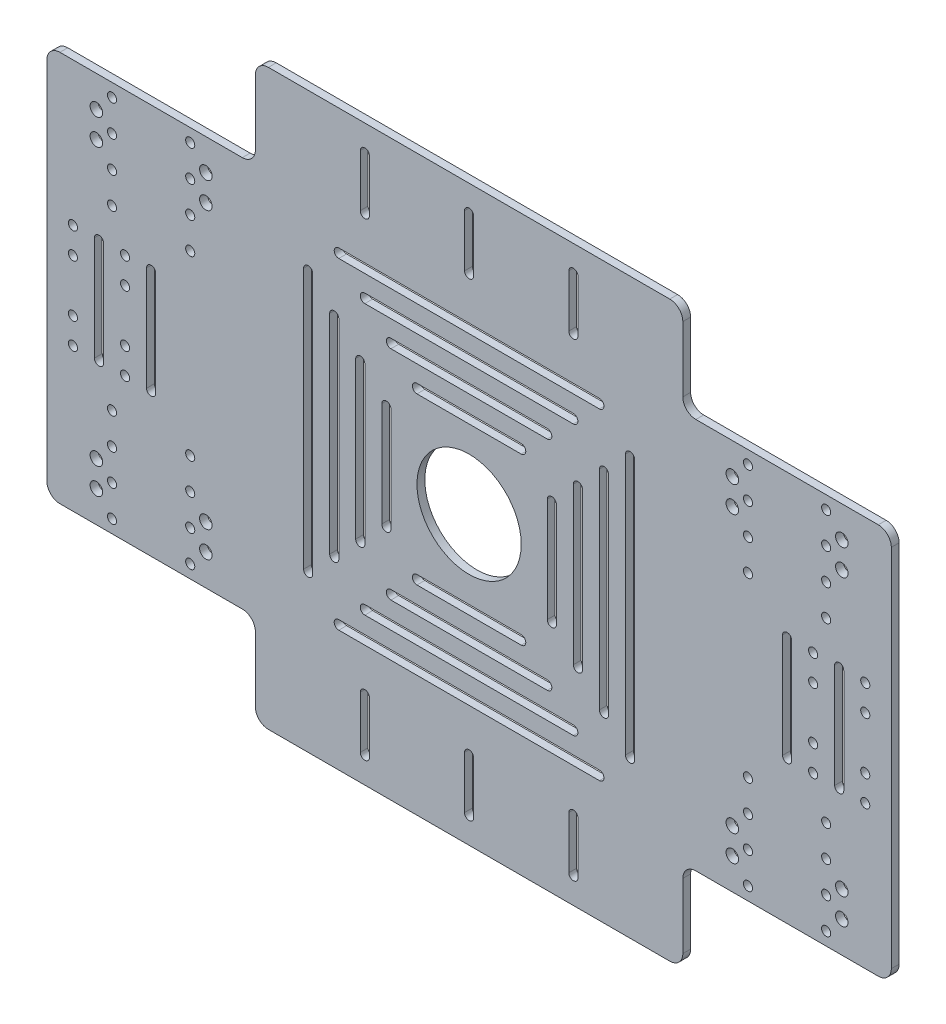
SolidWorks part; units mm, degrees
ref_plane "Front Plane" through (0, 0, 0) normal (0, 0, 1) x (1, 0, 0)
ref_plane "Top Plane" through (0, 0, 0) normal (0, 1, 0) x (1, 0, 0)
ref_plane "Right Plane" through (0, 0, 0) normal (1, 0, 0) x (0, 0, -1)
sketch "Model" plane through (0, 0, 0) normal (0, 0, 1) x (1, 0, 0)
  line L0 (-287, 200) -> (-287, -200)
  line L1 (-287, -200) -> (287, -200)
  line L2 (287, -200) -> (287, 200)
  line L3 (287, 200) -> (-287, 200)
  line L4 (287, -200) -> (287, -144)
  line L5 (287, -144) -> (107, -144)
  line L6 (107, -144) -> (107, -200)
  line L7 (287, -200) -> (107, -200)
  line L8 (187, -144) -> (187, -200)
  line L9 (237, -144) -> (237, -200)
  line L10 (187, -193) -> (107, -193)
  line L11 (187, -186) -> (107, -186)
  line L12 (187, -179) -> (107, -179)
  line L13 (147, -172) -> (147, -200)
  line L14 (213, -172) -> (213, -191)
  line L15 (225, -172) -> (225, -191)
  line L16 (237, -172) -> (107, -172)
  line L17 (287, -179) -> (237, -179)
  line L18 (287, -161) -> (237, -161)
  line L19 (287, -191) -> (187, -191)
  line L20 (-119.2105, 180.4807) -> (-119.2105, 155.4807)
  line L21 (-119.2105, -4.5193) -> (-119.2105, -29.5193)
  line L22 (44.7895, -29.5193) -> (44.7895, -4.5193)
  line L23 (44.7895, 155.4807) -> (44.7895, 180.4807)
  line L24 (39.7895, 185.4807) -> (-99.2105, 185.4807)
  line L25 (-99.2105, 185.4807) -> (-114.2105, 185.4807)
  line L26 (-114.2105, -34.5193) -> (-96.2105, -34.5193)
  line L27 (-96.2105, -34.5193) -> (39.7895, -34.5193)
  line L28 (124.7895, 5.4807) -> (124.7895, 76.9807)
  line L29 (124.7895, 76.9807) -> (124.7895, 145.4807)
  line L30 (-199.2105, 145.4807) -> (-199.2105, 76.9807)
  line L31 (-199.2105, 76.9807) -> (-199.2105, 5.4807)
  line L32 (-124.2105, 150.4807) -> (-194.2105, 150.4807)
  line L33 (-124.2105, 0.4807) -> (-194.2105, 0.4807)
  line L34 (49.7895, 0.4807) -> (119.7895, 0.4807)
  line L35 (49.7895, 150.4807) -> (119.7895, 150.4807)
  line L36 (-17.2105, 105.4807) -> (-37.2105, 105.4807)
  line L37 (-7.2105, 115.4807) -> (-37.2105, 115.4807)
  line L38 (2.7895, 125.4807) -> (-37.2105, 125.4807)
  line L39 (12.7895, 135.4807) -> (-37.2105, 135.4807)
  line L40 (-17.2105, 108.9807) -> (-37.2105, 108.9807)
  line L41 (-7.2105, 118.9807) -> (-37.2105, 118.9807)
  line L42 (2.7895, 128.9807) -> (-37.2105, 128.9807)
  line L43 (12.7895, 138.9807) -> (-37.2105, 138.9807)
  line L44 (-57.2105, 105.4807) -> (-37.2105, 105.4807)
  line L45 (-67.2105, 115.4807) -> (-37.2105, 115.4807)
  line L46 (-77.2105, 125.4807) -> (-37.2105, 125.4807)
  line L47 (-87.2105, 135.4807) -> (-37.2105, 135.4807)
  line L48 (-57.2105, 108.9807) -> (-37.2105, 108.9807)
  line L49 (-67.2105, 118.9807) -> (-37.2105, 118.9807)
  line L50 (-77.2105, 128.9807) -> (-37.2105, 128.9807)
  line L51 (-87.2105, 138.9807) -> (-37.2105, 138.9807)
  line L52 (-67.2105, 95.4807) -> (-67.2105, 75.4807)
  line L53 (-77.2105, 105.4807) -> (-77.2105, 75.4807)
  line L54 (-87.2105, 115.4807) -> (-87.2105, 75.4807)
  line L55 (-97.2105, 125.4807) -> (-97.2105, 75.4807)
  line L56 (-70.7105, 95.4807) -> (-70.7105, 75.4807)
  line L57 (-80.7105, 105.4807) -> (-80.7105, 75.4807)
  line L58 (-90.7105, 115.4807) -> (-90.7105, 75.4807)
  line L59 (-100.7105, 125.4807) -> (-100.7105, 75.4807)
  line L60 (-67.2105, 55.4807) -> (-67.2105, 75.4807)
  line L61 (-77.2105, 45.4807) -> (-77.2105, 75.4807)
  line L62 (-87.2105, 35.4807) -> (-87.2105, 75.4807)
  line L63 (-97.2105, 25.4807) -> (-97.2105, 75.4807)
  line L64 (-70.7105, 55.4807) -> (-70.7105, 75.4807)
  line L65 (-80.7105, 45.4807) -> (-80.7105, 75.4807)
  line L66 (-90.7105, 35.4807) -> (-90.7105, 75.4807)
  line L67 (-100.7105, 25.4807) -> (-100.7105, 75.4807)
  line L68 (-57.2105, 45.4807) -> (-37.2105, 45.4807)
  line L69 (-67.2105, 35.4807) -> (-37.2105, 35.4807)
  line L70 (-77.2105, 25.4807) -> (-37.2105, 25.4807)
  line L71 (-87.2105, 15.4807) -> (-37.2105, 15.4807)
  line L72 (-57.2105, 41.9807) -> (-37.2105, 41.9807)
  line L73 (-67.2105, 31.9807) -> (-37.2105, 31.9807)
  line L74 (-77.2105, 21.9807) -> (-37.2105, 21.9807)
  line L75 (-87.2105, 11.9807) -> (-37.2105, 11.9807)
  line L76 (-17.2105, 45.4807) -> (-37.2105, 45.4807)
  line L77 (-7.2105, 35.4807) -> (-37.2105, 35.4807)
  line L78 (2.7895, 25.4807) -> (-37.2105, 25.4807)
  line L79 (12.7895, 15.4807) -> (-37.2105, 15.4807)
  line L80 (-17.2105, 41.9807) -> (-37.2105, 41.9807)
  line L81 (-7.2105, 31.9807) -> (-37.2105, 31.9807)
  line L82 (2.7895, 21.9807) -> (-37.2105, 21.9807)
  line L83 (12.7895, 11.9807) -> (-37.2105, 11.9807)
  line L84 (-7.2105, 55.4807) -> (-7.2105, 75.4807)
  line L85 (2.7895, 45.4807) -> (2.7895, 75.4807)
  line L86 (12.7895, 35.4807) -> (12.7895, 75.4807)
  line L87 (22.7895, 25.4807) -> (22.7895, 75.4807)
  line L88 (-3.7105, 55.4807) -> (-3.7105, 75.4807)
  line L89 (6.2895, 45.4807) -> (6.2895, 75.4807)
  line L90 (16.2895, 35.4807) -> (16.2895, 75.4807)
  line L91 (26.2895, 25.4807) -> (26.2895, 75.4807)
  line L92 (-7.2105, 95.4807) -> (-7.2105, 75.4807)
  line L93 (2.7895, 105.4807) -> (2.7895, 75.4807)
  line L94 (12.7895, 115.4807) -> (12.7895, 75.4807)
  line L95 (22.7895, 125.4807) -> (22.7895, 75.4807)
  line L96 (-3.7105, 95.4807) -> (-3.7105, 75.4807)
  line L97 (6.2895, 105.4807) -> (6.2895, 75.4807)
  line L98 (16.2895, 115.4807) -> (16.2895, 75.4807)
  line L99 (26.2895, 125.4807) -> (26.2895, 75.4807)
  line L100 (-180.9605, 95.4807) -> (-180.9605, 55.4807)
  line L101 (-177.4605, 95.4807) -> (-177.4605, 55.4807)
  line L102 (-160.9605, 95.4807) -> (-160.9605, 55.4807)
  line L103 (-157.4605, 95.4807) -> (-157.4605, 55.4807)
  line L104 (106.5395, 95.4807) -> (106.5395, 55.4807)
  line L105 (103.0395, 95.4807) -> (103.0395, 55.4807)
  line L106 (86.5395, 95.4807) -> (86.5395, 55.4807)
  line L107 (83.0395, 95.4807) -> (83.0395, 55.4807)
  line L108 (-78.9605, 175.4807) -> (-78.9605, 155.4807)
  line L109 (-75.4605, 175.4807) -> (-75.4605, 155.4807)
  line L110 (-38.9605, 175.4807) -> (-38.9605, 155.4807)
  line L111 (-35.4605, 175.4807) -> (-35.4605, 155.4807)
  line L112 (4.5395, 175.4807) -> (4.5395, 155.4807)
  line L113 (1.0395, 175.4807) -> (1.0395, 155.4807)
  line L114 (-78.9605, -24.5193) -> (-78.9605, -4.5193)
  line L115 (-75.4605, -24.5193) -> (-75.4605, -4.5193)
  line L116 (-38.9605, -24.5193) -> (-38.9605, -4.5193)
  line L117 (-35.4605, -24.5193) -> (-35.4605, -4.5193)
  line L118 (4.5395, -24.5193) -> (4.5395, -4.5193)
  line L119 (1.0395, -24.5193) -> (1.0395, -4.5193)
  line L120 (210.9858, 185.4807) -> (213.9858, 185.4807)
  line L121 (213.9858, 185.4807) -> (213.9858, -33.4042)
  line L122 (210.9858, 185.4807) -> (210.9858, -33.4042)
  line L123 (210.9858, -33.4042) -> (213.9858, -33.4042)
  line L124 (210.9858, 150.4807) -> (213.9858, 150.4807)
  line L125 (210.9858, 0.4807) -> (213.9858, 0.4807)
  circle A0 centre (-180.2105, 138.4807) radius 2.4
  circle A1 centre (-138.2105, 138.4807) radius 2.4
  circle A2 centre (-180.2105, 128.4807) radius 2.4
  circle A3 centre (-138.2105, 128.4807) radius 2.4
  circle A4 centre (-180.2105, 12.4807) radius 2.4
  circle A5 centre (-138.2105, 12.4807) radius 2.4
  circle A6 centre (-180.2105, 22.4807) radius 2.4
  circle A7 centre (-138.2105, 22.4807) radius 2.4
  circle A8 centre (105.7895, 12.4807) radius 2.4
  circle A9 centre (63.7895, 12.4807) radius 2.4
  circle A10 centre (105.7895, 22.4807) radius 2.4
  circle A11 centre (63.7895, 22.4807) radius 2.4
  circle A12 centre (105.7895, 138.4807) radius 2.4
  circle A13 centre (63.7895, 138.4807) radius 2.4
  circle A14 centre (105.7895, 128.4807) radius 2.4
  circle A15 centre (63.7895, 128.4807) radius 2.4
  circle A16 centre (-144.2105, 17.4807) radius 1.75
  circle A17 centre (-144.2105, 5.4807) radius 1.75
  circle A18 centre (-144.2105, 29.4807) radius 1.75
  circle A19 centre (-144.2105, 41.4807) radius 1.75
  circle A20 centre (-174.2105, 17.4807) radius 1.75
  circle A21 centre (-174.2105, 5.4807) radius 1.75
  circle A22 centre (-174.2105, 29.4807) radius 1.75
  circle A23 centre (-174.2105, 41.4807) radius 1.75
  circle A24 centre (-144.2105, 133.4807) radius 1.75
  circle A25 centre (-144.2105, 145.4807) radius 1.75
  circle A26 centre (-144.2105, 121.4807) radius 1.75
  circle A27 centre (-144.2105, 109.4807) radius 1.75
  circle A28 centre (-174.2105, 133.4807) radius 1.75
  circle A29 centre (-174.2105, 145.4807) radius 1.75
  circle A30 centre (-174.2105, 121.4807) radius 1.75
  circle A31 centre (-174.2105, 109.4807) radius 1.75
  circle A32 centre (69.7895, 133.4807) radius 1.75
  circle A33 centre (69.7895, 145.4807) radius 1.75
  circle A34 centre (69.7895, 121.4807) radius 1.75
  circle A35 centre (69.7895, 109.4807) radius 1.75
  circle A36 centre (99.7895, 133.4807) radius 1.75
  circle A37 centre (99.7895, 145.4807) radius 1.75
  circle A38 centre (99.7895, 121.4807) radius 1.75
  circle A39 centre (99.7895, 109.4807) radius 1.75
  circle A40 centre (69.7895, 17.4807) radius 1.75
  circle A41 centre (69.7895, 5.4807) radius 1.75
  circle A42 centre (69.7895, 29.4807) radius 1.75
  circle A43 centre (69.7895, 41.4807) radius 1.75
  circle A44 centre (99.7895, 17.4807) radius 1.75
  circle A45 centre (99.7895, 5.4807) radius 1.75
  circle A46 centre (99.7895, 29.4807) radius 1.75
  circle A47 centre (99.7895, 41.4807) radius 1.75
  arc A48 (-194.2105, 150.4807) -> (-199.2105, 145.4807) centre (-194.2105, 145.4807) ccw
  arc A49 (-124.2105, 150.4807) -> (-119.2105, 155.4807) centre (-124.2105, 155.4807) ccw
  arc A50 (-199.2105, 5.4807) -> (-194.2105, 0.4807) centre (-194.2105, 5.4807) ccw
  arc A51 (-119.2105, -4.5193) -> (-124.2105, 0.4807) centre (-124.2105, -4.5193) ccw
  arc A52 (-119.2105, -29.5193) -> (-114.2105, -34.5193) centre (-114.2105, -29.5193) ccw
  arc A53 (39.7895, -34.5193) -> (44.7895, -29.5193) centre (39.7895, -29.5193) ccw
  arc A54 (49.7895, 0.4807) -> (44.7895, -4.5193) centre (49.7895, -4.5193) ccw
  arc A55 (119.7895, 0.4807) -> (124.7895, 5.4807) centre (119.7895, 5.4807) ccw
  arc A56 (124.7895, 145.4807) -> (119.7895, 150.4807) centre (119.7895, 145.4807) ccw
  arc A57 (44.7895, 155.4807) -> (49.7895, 150.4807) centre (49.7895, 155.4807) ccw
  arc A58 (44.7895, 180.4807) -> (39.7895, 185.4807) centre (39.7895, 180.4807) ccw
  arc A59 (-114.2105, 185.4807) -> (-119.2105, 180.4807) centre (-114.2105, 180.4807) ccw
  circle A60 centre (-37.2105, 75.4807) radius 20
  arc A61 (12.7895, 135.4807) -> (12.7895, 138.9807) centre (12.7895, 137.2307) ccw
  arc A62 (2.7895, 125.4807) -> (2.7895, 128.9807) centre (2.7895, 127.2307) ccw
  arc A63 (-7.2105, 115.4807) -> (-7.2105, 118.9807) centre (-7.2105, 117.2307) ccw
  arc A64 (-17.2105, 105.4807) -> (-17.2105, 108.9807) centre (-17.2105, 107.2307) ccw
  arc A65 (-87.2105, 138.9807) -> (-87.2105, 135.4807) centre (-87.2105, 137.2307) ccw
  arc A66 (-77.2105, 128.9807) -> (-77.2105, 125.4807) centre (-77.2105, 127.2307) ccw
  arc A67 (-67.2105, 118.9807) -> (-67.2105, 115.4807) centre (-67.2105, 117.2307) ccw
  arc A68 (-57.2105, 108.9807) -> (-57.2105, 105.4807) centre (-57.2105, 107.2307) ccw
  arc A69 (-97.2105, 125.4807) -> (-100.7105, 125.4807) centre (-98.9605, 125.4807) ccw
  arc A70 (-87.2105, 115.4807) -> (-90.7105, 115.4807) centre (-88.9605, 115.4807) ccw
  arc A71 (-77.2105, 105.4807) -> (-80.7105, 105.4807) centre (-78.9605, 105.4807) ccw
  arc A72 (-67.2105, 95.4807) -> (-70.7105, 95.4807) centre (-68.9605, 95.4807) ccw
  arc A73 (-100.7105, 25.4807) -> (-97.2105, 25.4807) centre (-98.9605, 25.4807) ccw
  arc A74 (-90.7105, 35.4807) -> (-87.2105, 35.4807) centre (-88.9605, 35.4807) ccw
  arc A75 (-80.7105, 45.4807) -> (-77.2105, 45.4807) centre (-78.9605, 45.4807) ccw
  arc A76 (-70.7105, 55.4807) -> (-67.2105, 55.4807) centre (-68.9605, 55.4807) ccw
  arc A77 (-87.2105, 15.4807) -> (-87.2105, 11.9807) centre (-87.2105, 13.7307) ccw
  arc A78 (-77.2105, 25.4807) -> (-77.2105, 21.9807) centre (-77.2105, 23.7307) ccw
  arc A79 (-67.2105, 35.4807) -> (-67.2105, 31.9807) centre (-67.2105, 33.7307) ccw
  arc A80 (-57.2105, 45.4807) -> (-57.2105, 41.9807) centre (-57.2105, 43.7307) ccw
  arc A81 (12.7895, 11.9807) -> (12.7895, 15.4807) centre (12.7895, 13.7307) ccw
  arc A82 (2.7895, 21.9807) -> (2.7895, 25.4807) centre (2.7895, 23.7307) ccw
  arc A83 (-7.2105, 31.9807) -> (-7.2105, 35.4807) centre (-7.2105, 33.7307) ccw
  arc A84 (-17.2105, 41.9807) -> (-17.2105, 45.4807) centre (-17.2105, 43.7307) ccw
  arc A85 (22.7895, 25.4807) -> (26.2895, 25.4807) centre (24.5395, 25.4807) ccw
  arc A86 (12.7895, 35.4807) -> (16.2895, 35.4807) centre (14.5395, 35.4807) ccw
  arc A87 (2.7895, 45.4807) -> (6.2895, 45.4807) centre (4.5395, 45.4807) ccw
  arc A88 (-7.2105, 55.4807) -> (-3.7105, 55.4807) centre (-5.4605, 55.4807) ccw
  arc A89 (26.2895, 125.4807) -> (22.7895, 125.4807) centre (24.5395, 125.4807) ccw
  arc A90 (16.2895, 115.4807) -> (12.7895, 115.4807) centre (14.5395, 115.4807) ccw
  arc A91 (6.2895, 105.4807) -> (2.7895, 105.4807) centre (4.5395, 105.4807) ccw
  arc A92 (-3.7105, 95.4807) -> (-7.2105, 95.4807) centre (-5.4605, 95.4807) ccw
  circle A93 centre (-189.2105, 85.4807) radius 1.75
  circle A94 centre (-189.2105, 95.4807) radius 1.75
  circle A95 centre (-169.2105, 95.4807) radius 1.75
  circle A96 centre (-169.2105, 85.4807) radius 1.75
  circle A97 centre (-189.2105, 65.4807) radius 1.75
  circle A98 centre (-189.2105, 55.4807) radius 1.75
  circle A99 centre (-169.2105, 55.4807) radius 1.75
  circle A100 centre (-169.2105, 65.4807) radius 1.75
  arc A101 (-177.4605, 95.4807) -> (-180.9605, 95.4807) centre (-179.2105, 95.4807) ccw
  arc A102 (-180.9605, 55.4807) -> (-177.4605, 55.4807) centre (-179.2105, 55.4807) ccw
  arc A103 (-160.9605, 55.4807) -> (-157.4605, 55.4807) centre (-159.2105, 55.4807) ccw
  arc A104 (-157.4605, 95.4807) -> (-160.9605, 95.4807) centre (-159.2105, 95.4807) ccw
  circle A105 centre (114.7895, 85.4807) radius 1.75
  circle A106 centre (114.7895, 95.4807) radius 1.75
  circle A107 centre (94.7895, 95.4807) radius 1.75
  circle A108 centre (94.7895, 85.4807) radius 1.75
  circle A109 centre (114.7895, 65.4807) radius 1.75
  circle A110 centre (114.7895, 55.4807) radius 1.75
  circle A111 centre (94.7895, 55.4807) radius 1.75
  circle A112 centre (94.7895, 65.4807) radius 1.75
  arc A113 (106.5395, 95.4807) -> (103.0395, 95.4807) centre (104.7895, 95.4807) ccw
  arc A114 (103.0395, 55.4807) -> (106.5395, 55.4807) centre (104.7895, 55.4807) ccw
  arc A115 (83.0395, 55.4807) -> (86.5395, 55.4807) centre (84.7895, 55.4807) ccw
  arc A116 (86.5395, 95.4807) -> (83.0395, 95.4807) centre (84.7895, 95.4807) ccw
  arc A117 (-75.4605, 175.4807) -> (-78.9605, 175.4807) centre (-77.2105, 175.4807) ccw
  arc A118 (-78.9605, 155.4807) -> (-75.4605, 155.4807) centre (-77.2105, 155.4807) ccw
  arc A119 (-38.9605, 155.4807) -> (-35.4605, 155.4807) centre (-37.2105, 155.4807) ccw
  arc A120 (-35.4605, 175.4807) -> (-38.9605, 175.4807) centre (-37.2105, 175.4807) ccw
  arc A121 (4.5395, 175.4807) -> (1.0395, 175.4807) centre (2.7895, 175.4807) ccw
  arc A122 (1.0395, 155.4807) -> (4.5395, 155.4807) centre (2.7895, 155.4807) ccw
  arc A123 (-78.9605, -24.5193) -> (-75.4605, -24.5193) centre (-77.2105, -24.5193) ccw
  arc A124 (-75.4605, -4.5193) -> (-78.9605, -4.5193) centre (-77.2105, -4.5193) ccw
  arc A125 (-35.4605, -4.5193) -> (-38.9605, -4.5193) centre (-37.2105, -4.5193) ccw
  arc A126 (-38.9605, -24.5193) -> (-35.4605, -24.5193) centre (-37.2105, -24.5193) ccw
  arc A127 (1.0395, -24.5193) -> (4.5395, -24.5193) centre (2.7895, -24.5193) ccw
  arc A128 (4.5395, -4.5193) -> (1.0395, -4.5193) centre (2.7895, -4.5193) ccw
sketch "Sketch2" plane through (0, 0, 0) normal (0, 0, 1) x (1, 0, 0)
  line L0 (-124.2105, 150.4807) -> (-194.2105, 150.4807) construction
  line L1 (-119.2105, 180.4807) -> (-119.2105, 155.4807) construction
  line L2 (-99.2105, 185.4807) -> (-114.2105, 185.4807) construction
  line L3 (39.7895, 185.4807) -> (-99.2105, 185.4807) construction
  line L4 (44.7895, 155.4807) -> (44.7895, 180.4807) construction
  line L5 (49.7895, 150.4807) -> (119.7895, 150.4807) construction
  line L6 (124.7895, 76.9807) -> (124.7895, 145.4807) construction
  line L7 (124.7895, 5.4807) -> (124.7895, 76.9807) construction
  line L8 (49.7895, 0.4807) -> (119.7895, 0.4807) construction
  line L9 (44.7895, -29.5193) -> (44.7895, -4.5193) construction
  line L10 (-96.2105, -34.5193) -> (39.7895, -34.5193) construction
  line L11 (-114.2105, -34.5193) -> (-96.2105, -34.5193) construction
  line L12 (-119.2105, -4.5193) -> (-119.2105, -29.5193) construction
  line L13 (-124.2105, 0.4807) -> (-194.2105, 0.4807) construction
  line L14 (-199.2105, 76.9807) -> (-199.2105, 5.4807) construction
  line L15 (-199.2105, 145.4807) -> (-199.2105, 76.9807) construction
  line L16 (-124.2105, 150.4807) -> (-194.2105, 150.4807)
  line L17 (-119.2105, 180.4807) -> (-119.2105, 155.4807)
  line L18 (-99.2105, 185.4807) -> (-114.2105, 185.4807)
  line L19 (39.7895, 185.4807) -> (-99.2105, 185.4807)
  line L20 (44.7895, 155.4807) -> (44.7895, 180.4807)
  line L21 (49.7895, 150.4807) -> (119.7895, 150.4807)
  line L22 (124.7895, 76.9807) -> (124.7895, 145.4807)
  line L23 (124.7895, 5.4807) -> (124.7895, 76.9807)
  line L24 (49.7895, 0.4807) -> (119.7895, 0.4807)
  line L25 (44.7895, -29.5193) -> (44.7895, -4.5193)
  line L26 (-96.2105, -34.5193) -> (39.7895, -34.5193)
  line L27 (-114.2105, -34.5193) -> (-96.2105, -34.5193)
  line L28 (-119.2105, -4.5193) -> (-119.2105, -29.5193)
  line L29 (-124.2105, 0.4807) -> (-194.2105, 0.4807)
  line L30 (-199.2105, 76.9807) -> (-199.2105, 5.4807)
  line L31 (-199.2105, 145.4807) -> (-199.2105, 76.9807)
  line L32 (-78.9605, 175.4807) -> (-78.9605, 155.4807) construction
  line L33 (-75.4605, 175.4807) -> (-75.4605, 155.4807) construction
  line L34 (-78.9605, 175.4807) -> (-78.9605, 155.4807)
  line L35 (-75.4605, 175.4807) -> (-75.4605, 155.4807)
  line L36 (-38.9605, 175.4807) -> (-38.9605, 155.4807) construction
  line L37 (-35.4605, 175.4807) -> (-35.4605, 155.4807) construction
  line L38 (-38.9605, 175.4807) -> (-38.9605, 155.4807)
  line L39 (-35.4605, 175.4807) -> (-35.4605, 155.4807)
  line L40 (4.5395, 175.4807) -> (4.5395, 155.4807) construction
  line L41 (1.0395, 175.4807) -> (1.0395, 155.4807) construction
  line L42 (4.5395, 175.4807) -> (4.5395, 155.4807)
  line L43 (1.0395, 175.4807) -> (1.0395, 155.4807)
  line L44 (-87.2105, 138.9807) -> (-37.2105, 138.9807) construction
  line L45 (12.7895, 138.9807) -> (-37.2105, 138.9807) construction
  line L46 (12.7895, 135.4807) -> (-37.2105, 135.4807) construction
  line L47 (-87.2105, 135.4807) -> (-37.2105, 135.4807) construction
  line L48 (-87.2105, 138.9807) -> (-37.2105, 138.9807)
  line L49 (12.7895, 138.9807) -> (-37.2105, 138.9807)
  line L50 (12.7895, 135.4807) -> (-37.2105, 135.4807)
  line L51 (-87.2105, 135.4807) -> (-37.2105, 135.4807)
  line L52 (-77.2105, 128.9807) -> (-37.2105, 128.9807) construction
  line L53 (2.7895, 128.9807) -> (-37.2105, 128.9807) construction
  line L54 (2.7895, 125.4807) -> (-37.2105, 125.4807) construction
  line L55 (-77.2105, 125.4807) -> (-37.2105, 125.4807) construction
  line L56 (-77.2105, 128.9807) -> (-37.2105, 128.9807)
  line L57 (2.7895, 128.9807) -> (-37.2105, 128.9807)
  line L58 (2.7895, 125.4807) -> (-37.2105, 125.4807)
  line L59 (-77.2105, 125.4807) -> (-37.2105, 125.4807)
  line L60 (-67.2105, 118.9807) -> (-37.2105, 118.9807) construction
  line L61 (-7.2105, 118.9807) -> (-37.2105, 118.9807) construction
  line L62 (-7.2105, 115.4807) -> (-37.2105, 115.4807) construction
  line L63 (-67.2105, 115.4807) -> (-37.2105, 115.4807) construction
  line L64 (-67.2105, 118.9807) -> (-37.2105, 118.9807)
  line L65 (-7.2105, 118.9807) -> (-37.2105, 118.9807)
  line L66 (-7.2105, 115.4807) -> (-37.2105, 115.4807)
  line L67 (-67.2105, 115.4807) -> (-37.2105, 115.4807)
  line L68 (-57.2105, 108.9807) -> (-37.2105, 108.9807) construction
  line L69 (-17.2105, 108.9807) -> (-37.2105, 108.9807) construction
  line L70 (-17.2105, 105.4807) -> (-37.2105, 105.4807) construction
  line L71 (-57.2105, 105.4807) -> (-37.2105, 105.4807) construction
  line L72 (-57.2105, 108.9807) -> (-37.2105, 108.9807)
  line L73 (-17.2105, 108.9807) -> (-37.2105, 108.9807)
  line L74 (-17.2105, 105.4807) -> (-37.2105, 105.4807)
  line L75 (-57.2105, 105.4807) -> (-37.2105, 105.4807)
  line L76 (-100.7105, 25.4807) -> (-100.7105, 75.4807) construction
  line L77 (-100.7105, 125.4807) -> (-100.7105, 75.4807) construction
  line L78 (-97.2105, 125.4807) -> (-97.2105, 75.4807) construction
  line L79 (-97.2105, 25.4807) -> (-97.2105, 75.4807) construction
  line L80 (-100.7105, 25.4807) -> (-100.7105, 75.4807)
  line L81 (-100.7105, 125.4807) -> (-100.7105, 75.4807)
  line L82 (-97.2105, 125.4807) -> (-97.2105, 75.4807)
  line L83 (-97.2105, 25.4807) -> (-97.2105, 75.4807)
  line L84 (-90.7105, 115.4807) -> (-90.7105, 75.4807) construction
  line L85 (-90.7105, 35.4807) -> (-90.7105, 75.4807) construction
  line L86 (-87.2105, 35.4807) -> (-87.2105, 75.4807) construction
  line L87 (-87.2105, 115.4807) -> (-87.2105, 75.4807) construction
  line L88 (-90.7105, 115.4807) -> (-90.7105, 75.4807)
  line L89 (-90.7105, 35.4807) -> (-90.7105, 75.4807)
  line L90 (-87.2105, 35.4807) -> (-87.2105, 75.4807)
  line L91 (-87.2105, 115.4807) -> (-87.2105, 75.4807)
  line L92 (-80.7105, 105.4807) -> (-80.7105, 75.4807) construction
  line L93 (-80.7105, 45.4807) -> (-80.7105, 75.4807) construction
  line L94 (-77.2105, 45.4807) -> (-77.2105, 75.4807) construction
  line L95 (-77.2105, 105.4807) -> (-77.2105, 75.4807) construction
  line L96 (-80.7105, 105.4807) -> (-80.7105, 75.4807)
  line L97 (-80.7105, 45.4807) -> (-80.7105, 75.4807)
  line L98 (-77.2105, 45.4807) -> (-77.2105, 75.4807)
  line L99 (-77.2105, 105.4807) -> (-77.2105, 75.4807)
  line L100 (-70.7105, 95.4807) -> (-70.7105, 75.4807) construction
  line L101 (-70.7105, 55.4807) -> (-70.7105, 75.4807) construction
  line L102 (-67.2105, 55.4807) -> (-67.2105, 75.4807) construction
  line L103 (-67.2105, 95.4807) -> (-67.2105, 75.4807) construction
  line L104 (-70.7105, 95.4807) -> (-70.7105, 75.4807)
  line L105 (-70.7105, 55.4807) -> (-70.7105, 75.4807)
  line L106 (-67.2105, 55.4807) -> (-67.2105, 75.4807)
  line L107 (-67.2105, 95.4807) -> (-67.2105, 75.4807)
  line L108 (-160.9605, 95.4807) -> (-160.9605, 55.4807) construction
  line L109 (-157.4605, 95.4807) -> (-157.4605, 55.4807) construction
  line L110 (-160.9605, 95.4807) -> (-160.9605, 55.4807)
  line L111 (-157.4605, 95.4807) -> (-157.4605, 55.4807)
  line L112 (-180.9605, 95.4807) -> (-180.9605, 55.4807) construction
  line L113 (-177.4605, 95.4807) -> (-177.4605, 55.4807) construction
  line L114 (-180.9605, 95.4807) -> (-180.9605, 55.4807)
  line L115 (-177.4605, 95.4807) -> (-177.4605, 55.4807)
  line L116 (-57.2105, 45.4807) -> (-37.2105, 45.4807) construction
  line L117 (-17.2105, 45.4807) -> (-37.2105, 45.4807) construction
  line L118 (-17.2105, 41.9807) -> (-37.2105, 41.9807) construction
  line L119 (-57.2105, 41.9807) -> (-37.2105, 41.9807) construction
  line L120 (-67.2105, 35.4807) -> (-37.2105, 35.4807) construction
  line L121 (-7.2105, 35.4807) -> (-37.2105, 35.4807) construction
  line L122 (-7.2105, 31.9807) -> (-37.2105, 31.9807) construction
  line L123 (-67.2105, 31.9807) -> (-37.2105, 31.9807) construction
  line L124 (-77.2105, 25.4807) -> (-37.2105, 25.4807) construction
  line L125 (2.7895, 25.4807) -> (-37.2105, 25.4807) construction
  line L126 (2.7895, 21.9807) -> (-37.2105, 21.9807) construction
  line L127 (-77.2105, 21.9807) -> (-37.2105, 21.9807) construction
  line L128 (-87.2105, 15.4807) -> (-37.2105, 15.4807) construction
  line L129 (12.7895, 15.4807) -> (-37.2105, 15.4807) construction
  line L130 (12.7895, 11.9807) -> (-37.2105, 11.9807) construction
  line L131 (-87.2105, 11.9807) -> (-37.2105, 11.9807) construction
  line L132 (-57.2105, 45.4807) -> (-37.2105, 45.4807)
  line L133 (-17.2105, 45.4807) -> (-37.2105, 45.4807)
  line L134 (-17.2105, 41.9807) -> (-37.2105, 41.9807)
  line L135 (-57.2105, 41.9807) -> (-37.2105, 41.9807)
  line L136 (-67.2105, 35.4807) -> (-37.2105, 35.4807)
  line L137 (-7.2105, 35.4807) -> (-37.2105, 35.4807)
  line L138 (-7.2105, 31.9807) -> (-37.2105, 31.9807)
  line L139 (-67.2105, 31.9807) -> (-37.2105, 31.9807)
  line L140 (-77.2105, 25.4807) -> (-37.2105, 25.4807)
  line L141 (2.7895, 25.4807) -> (-37.2105, 25.4807)
  line L142 (2.7895, 21.9807) -> (-37.2105, 21.9807)
  line L143 (-77.2105, 21.9807) -> (-37.2105, 21.9807)
  line L144 (-87.2105, 15.4807) -> (-37.2105, 15.4807)
  line L145 (12.7895, 15.4807) -> (-37.2105, 15.4807)
  line L146 (12.7895, 11.9807) -> (-37.2105, 11.9807)
  line L147 (-87.2105, 11.9807) -> (-37.2105, 11.9807)
  line L148 (22.7895, 25.4807) -> (22.7895, 75.4807) construction
  line L149 (22.7895, 125.4807) -> (22.7895, 75.4807) construction
  line L150 (26.2895, 125.4807) -> (26.2895, 75.4807) construction
  line L151 (26.2895, 25.4807) -> (26.2895, 75.4807) construction
  line L152 (12.7895, 35.4807) -> (12.7895, 75.4807) construction
  line L153 (12.7895, 115.4807) -> (12.7895, 75.4807) construction
  line L154 (16.2895, 115.4807) -> (16.2895, 75.4807) construction
  line L155 (16.2895, 35.4807) -> (16.2895, 75.4807) construction
  line L156 (2.7895, 45.4807) -> (2.7895, 75.4807) construction
  line L157 (2.7895, 105.4807) -> (2.7895, 75.4807) construction
  line L158 (6.2895, 105.4807) -> (6.2895, 75.4807) construction
  line L159 (6.2895, 45.4807) -> (6.2895, 75.4807) construction
  line L160 (-7.2105, 55.4807) -> (-7.2105, 75.4807) construction
  line L161 (-7.2105, 95.4807) -> (-7.2105, 75.4807) construction
  line L162 (-3.7105, 95.4807) -> (-3.7105, 75.4807) construction
  line L163 (-3.7105, 55.4807) -> (-3.7105, 75.4807) construction
  line L164 (1.0395, -24.5193) -> (1.0395, -4.5193) construction
  line L165 (4.5395, -24.5193) -> (4.5395, -4.5193) construction
  line L166 (-38.9605, -24.5193) -> (-38.9605, -4.5193) construction
  line L167 (-35.4605, -24.5193) -> (-35.4605, -4.5193) construction
  line L168 (-78.9605, -24.5193) -> (-78.9605, -4.5193) construction
  line L169 (-75.4605, -24.5193) -> (-75.4605, -4.5193) construction
  line L170 (22.7895, 25.4807) -> (22.7895, 75.4807)
  line L171 (22.7895, 125.4807) -> (22.7895, 75.4807)
  line L172 (26.2895, 125.4807) -> (26.2895, 75.4807)
  line L173 (26.2895, 25.4807) -> (26.2895, 75.4807)
  line L174 (12.7895, 35.4807) -> (12.7895, 75.4807)
  line L175 (12.7895, 115.4807) -> (12.7895, 75.4807)
  line L176 (16.2895, 115.4807) -> (16.2895, 75.4807)
  line L177 (16.2895, 35.4807) -> (16.2895, 75.4807)
  line L178 (2.7895, 45.4807) -> (2.7895, 75.4807)
  line L179 (2.7895, 105.4807) -> (2.7895, 75.4807)
  line L180 (6.2895, 105.4807) -> (6.2895, 75.4807)
  line L181 (6.2895, 45.4807) -> (6.2895, 75.4807)
  line L182 (-7.2105, 55.4807) -> (-7.2105, 75.4807)
  line L183 (-7.2105, 95.4807) -> (-7.2105, 75.4807)
  line L184 (-3.7105, 95.4807) -> (-3.7105, 75.4807)
  line L185 (-3.7105, 55.4807) -> (-3.7105, 75.4807)
  line L186 (1.0395, -24.5193) -> (1.0395, -4.5193)
  line L187 (4.5395, -24.5193) -> (4.5395, -4.5193)
  line L188 (-38.9605, -24.5193) -> (-38.9605, -4.5193)
  line L189 (-35.4605, -24.5193) -> (-35.4605, -4.5193)
  line L190 (-78.9605, -24.5193) -> (-78.9605, -4.5193)
  line L191 (-75.4605, -24.5193) -> (-75.4605, -4.5193)
  line L192 (106.5395, 95.4807) -> (106.5395, 55.4807) construction
  line L193 (103.0395, 95.4807) -> (103.0395, 55.4807) construction
  line L194 (83.0395, 95.4807) -> (83.0395, 55.4807) construction
  line L195 (86.5395, 95.4807) -> (86.5395, 55.4807) construction
  line L196 (106.5395, 95.4807) -> (106.5395, 55.4807)
  line L197 (103.0395, 95.4807) -> (103.0395, 55.4807)
  line L198 (83.0395, 95.4807) -> (83.0395, 55.4807)
  line L199 (86.5395, 95.4807) -> (86.5395, 55.4807)
  arc A0 (-194.2105, 150.4807) -> (-199.2105, 145.4807) centre (-194.2105, 145.4807) ccw construction
  arc A1 (-124.2105, 150.4807) -> (-119.2105, 155.4807) centre (-124.2105, 155.4807) ccw construction
  arc A2 (-114.2105, 185.4807) -> (-119.2105, 180.4807) centre (-114.2105, 180.4807) ccw construction
  arc A3 (44.7895, 180.4807) -> (39.7895, 185.4807) centre (39.7895, 180.4807) ccw construction
  arc A4 (44.7895, 155.4807) -> (49.7895, 150.4807) centre (49.7895, 155.4807) ccw construction
  arc A5 (124.7895, 145.4807) -> (119.7895, 150.4807) centre (119.7895, 145.4807) ccw construction
  arc A6 (119.7895, 0.4807) -> (124.7895, 5.4807) centre (119.7895, 5.4807) ccw construction
  arc A7 (49.7895, 0.4807) -> (44.7895, -4.5193) centre (49.7895, -4.5193) ccw construction
  arc A8 (39.7895, -34.5193) -> (44.7895, -29.5193) centre (39.7895, -29.5193) ccw construction
  arc A9 (-119.2105, -29.5193) -> (-114.2105, -34.5193) centre (-114.2105, -29.5193) ccw construction
  arc A10 (-119.2105, -4.5193) -> (-124.2105, 0.4807) centre (-124.2105, -4.5193) ccw construction
  arc A11 (-199.2105, 5.4807) -> (-194.2105, 0.4807) centre (-194.2105, 5.4807) ccw construction
  arc A12 (-194.2105, 150.4807) -> (-199.2105, 145.4807) centre (-194.2105, 145.4807) ccw
  arc A13 (-124.2105, 150.4807) -> (-119.2105, 155.4807) centre (-124.2105, 155.4807) ccw
  arc A14 (-114.2105, 185.4807) -> (-119.2105, 180.4807) centre (-114.2105, 180.4807) ccw
  arc A15 (44.7895, 180.4807) -> (39.7895, 185.4807) centre (39.7895, 180.4807) ccw
  arc A16 (44.7895, 155.4807) -> (49.7895, 150.4807) centre (49.7895, 155.4807) ccw
  arc A17 (124.7895, 145.4807) -> (119.7895, 150.4807) centre (119.7895, 145.4807) ccw
  arc A18 (119.7895, 0.4807) -> (124.7895, 5.4807) centre (119.7895, 5.4807) ccw
  arc A19 (49.7895, 0.4807) -> (44.7895, -4.5193) centre (49.7895, -4.5193) ccw
  arc A20 (39.7895, -34.5193) -> (44.7895, -29.5193) centre (39.7895, -29.5193) ccw
  arc A21 (-119.2105, -29.5193) -> (-114.2105, -34.5193) centre (-114.2105, -29.5193) ccw
  arc A22 (-119.2105, -4.5193) -> (-124.2105, 0.4807) centre (-124.2105, -4.5193) ccw
  arc A23 (-199.2105, 5.4807) -> (-194.2105, 0.4807) centre (-194.2105, 5.4807) ccw
  arc A24 (-75.4605, 175.4807) -> (-78.9605, 175.4807) centre (-77.2105, 175.4807) ccw construction
  arc A25 (-78.9605, 155.4807) -> (-75.4605, 155.4807) centre (-77.2105, 155.4807) ccw construction
  arc A26 (-75.4605, 175.4807) -> (-78.9605, 175.4807) centre (-77.2105, 175.4807) ccw
  arc A27 (-78.9605, 155.4807) -> (-75.4605, 155.4807) centre (-77.2105, 155.4807) ccw
  arc A28 (-35.4605, 175.4807) -> (-38.9605, 175.4807) centre (-37.2105, 175.4807) ccw construction
  arc A29 (-38.9605, 155.4807) -> (-35.4605, 155.4807) centre (-37.2105, 155.4807) ccw construction
  arc A30 (-35.4605, 175.4807) -> (-38.9605, 175.4807) centre (-37.2105, 175.4807) ccw
  arc A31 (-38.9605, 155.4807) -> (-35.4605, 155.4807) centre (-37.2105, 155.4807) ccw
  arc A32 (4.5395, 175.4807) -> (1.0395, 175.4807) centre (2.7895, 175.4807) ccw construction
  arc A33 (1.0395, 155.4807) -> (4.5395, 155.4807) centre (2.7895, 155.4807) ccw construction
  arc A34 (4.5395, 175.4807) -> (1.0395, 175.4807) centre (2.7895, 175.4807) ccw
  arc A35 (1.0395, 155.4807) -> (4.5395, 155.4807) centre (2.7895, 155.4807) ccw
  arc A36 (-87.2105, 138.9807) -> (-87.2105, 135.4807) centre (-87.2105, 137.2307) ccw construction
  arc A37 (12.7895, 135.4807) -> (12.7895, 138.9807) centre (12.7895, 137.2307) ccw construction
  arc A38 (-87.2105, 138.9807) -> (-87.2105, 135.4807) centre (-87.2105, 137.2307) ccw
  arc A39 (12.7895, 135.4807) -> (12.7895, 138.9807) centre (12.7895, 137.2307) ccw
  arc A40 (-77.2105, 128.9807) -> (-77.2105, 125.4807) centre (-77.2105, 127.2307) ccw construction
  arc A41 (2.7895, 125.4807) -> (2.7895, 128.9807) centre (2.7895, 127.2307) ccw construction
  arc A42 (-77.2105, 128.9807) -> (-77.2105, 125.4807) centre (-77.2105, 127.2307) ccw
  arc A43 (2.7895, 125.4807) -> (2.7895, 128.9807) centre (2.7895, 127.2307) ccw
  arc A44 (-67.2105, 118.9807) -> (-67.2105, 115.4807) centre (-67.2105, 117.2307) ccw construction
  arc A45 (-7.2105, 115.4807) -> (-7.2105, 118.9807) centre (-7.2105, 117.2307) ccw construction
  arc A46 (-67.2105, 118.9807) -> (-67.2105, 115.4807) centre (-67.2105, 117.2307) ccw
  arc A47 (-7.2105, 115.4807) -> (-7.2105, 118.9807) centre (-7.2105, 117.2307) ccw
  arc A48 (-57.2105, 108.9807) -> (-57.2105, 105.4807) centre (-57.2105, 107.2307) ccw construction
  arc A49 (-17.2105, 105.4807) -> (-17.2105, 108.9807) centre (-17.2105, 107.2307) ccw construction
  arc A50 (-57.2105, 108.9807) -> (-57.2105, 105.4807) centre (-57.2105, 107.2307) ccw
  arc A51 (-17.2105, 105.4807) -> (-17.2105, 108.9807) centre (-17.2105, 107.2307) ccw
  circle A52 centre (-37.2105, 75.4807) radius 20 construction
  circle A53 centre (-37.2105, 75.4807) radius 20
  arc A54 (-100.7105, 25.4807) -> (-97.2105, 25.4807) centre (-98.9605, 25.4807) ccw construction
  arc A55 (-97.2105, 125.4807) -> (-100.7105, 125.4807) centre (-98.9605, 125.4807) ccw construction
  arc A56 (-100.7105, 25.4807) -> (-97.2105, 25.4807) centre (-98.9605, 25.4807) ccw
  arc A57 (-97.2105, 125.4807) -> (-100.7105, 125.4807) centre (-98.9605, 125.4807) ccw
  arc A58 (-87.2105, 115.4807) -> (-90.7105, 115.4807) centre (-88.9605, 115.4807) ccw construction
  arc A59 (-90.7105, 35.4807) -> (-87.2105, 35.4807) centre (-88.9605, 35.4807) ccw construction
  arc A60 (-87.2105, 115.4807) -> (-90.7105, 115.4807) centre (-88.9605, 115.4807) ccw
  arc A61 (-90.7105, 35.4807) -> (-87.2105, 35.4807) centre (-88.9605, 35.4807) ccw
  arc A62 (-77.2105, 105.4807) -> (-80.7105, 105.4807) centre (-78.9605, 105.4807) ccw construction
  arc A63 (-80.7105, 45.4807) -> (-77.2105, 45.4807) centre (-78.9605, 45.4807) ccw construction
  arc A64 (-77.2105, 105.4807) -> (-80.7105, 105.4807) centre (-78.9605, 105.4807) ccw
  arc A65 (-80.7105, 45.4807) -> (-77.2105, 45.4807) centre (-78.9605, 45.4807) ccw
  arc A66 (-67.2105, 95.4807) -> (-70.7105, 95.4807) centre (-68.9605, 95.4807) ccw construction
  arc A67 (-70.7105, 55.4807) -> (-67.2105, 55.4807) centre (-68.9605, 55.4807) ccw construction
  arc A68 (-67.2105, 95.4807) -> (-70.7105, 95.4807) centre (-68.9605, 95.4807) ccw
  arc A69 (-70.7105, 55.4807) -> (-67.2105, 55.4807) centre (-68.9605, 55.4807) ccw
  arc A70 (-157.4605, 95.4807) -> (-160.9605, 95.4807) centre (-159.2105, 95.4807) ccw construction
  arc A71 (-160.9605, 55.4807) -> (-157.4605, 55.4807) centre (-159.2105, 55.4807) ccw construction
  arc A72 (-157.4605, 95.4807) -> (-160.9605, 95.4807) centre (-159.2105, 95.4807) ccw
  arc A73 (-160.9605, 55.4807) -> (-157.4605, 55.4807) centre (-159.2105, 55.4807) ccw
  arc A74 (-177.4605, 95.4807) -> (-180.9605, 95.4807) centre (-179.2105, 95.4807) ccw construction
  arc A75 (-180.9605, 55.4807) -> (-177.4605, 55.4807) centre (-179.2105, 55.4807) ccw construction
  arc A76 (-177.4605, 95.4807) -> (-180.9605, 95.4807) centre (-179.2105, 95.4807) ccw
  arc A77 (-180.9605, 55.4807) -> (-177.4605, 55.4807) centre (-179.2105, 55.4807) ccw
  circle A78 centre (-144.2105, 41.4807) radius 1.75 construction
  circle A79 centre (-144.2105, 29.4807) radius 1.75 construction
  circle A80 centre (-144.2105, 17.4807) radius 1.75 construction
  circle A81 centre (-144.2105, 5.4807) radius 1.75 construction
  circle A82 centre (-138.2105, 12.4807) radius 2.4 construction
  circle A83 centre (-138.2105, 22.4807) radius 2.4 construction
  circle A84 centre (-180.2105, 22.4807) radius 2.4 construction
  circle A85 centre (-180.2105, 12.4807) radius 2.4 construction
  circle A86 centre (-174.2105, 5.4807) radius 1.75 construction
  circle A87 centre (-174.2105, 17.4807) radius 1.75 construction
  circle A88 centre (-174.2105, 29.4807) radius 1.75 construction
  circle A89 centre (-174.2105, 41.4807) radius 1.75 construction
  circle A90 centre (-189.2105, 95.4807) radius 1.75 construction
  circle A91 centre (-189.2105, 85.4807) radius 1.75 construction
  circle A92 centre (-189.2105, 65.4807) radius 1.75 construction
  circle A93 centre (-189.2105, 55.4807) radius 1.75 construction
  circle A94 centre (-169.2105, 55.4807) radius 1.75 construction
  circle A95 centre (-169.2105, 65.4807) radius 1.75 construction
  circle A96 centre (-169.2105, 85.4807) radius 1.75 construction
  circle A97 centre (-169.2105, 95.4807) radius 1.75 construction
  circle A98 centre (-138.2105, 138.4807) radius 2.4 construction
  circle A99 centre (-144.2105, 145.4807) radius 1.75 construction
  circle A100 centre (-144.2105, 133.4807) radius 1.75 construction
  circle A101 centre (-138.2105, 128.4807) radius 2.4 construction
  circle A102 centre (-144.2105, 121.4807) radius 1.75 construction
  circle A103 centre (-144.2105, 109.4807) radius 1.75 construction
  circle A104 centre (-174.2105, 109.4807) radius 1.75 construction
  circle A105 centre (-174.2105, 121.4807) radius 1.75 construction
  circle A106 centre (-180.2105, 128.4807) radius 2.4 construction
  circle A107 centre (-174.2105, 133.4807) radius 1.75 construction
  circle A108 centre (-180.2105, 138.4807) radius 2.4 construction
  circle A109 centre (-174.2105, 145.4807) radius 1.75 construction
  circle A110 centre (-144.2105, 41.4807) radius 1.75
  circle A111 centre (-144.2105, 29.4807) radius 1.75
  circle A112 centre (-144.2105, 17.4807) radius 1.75
  circle A113 centre (-144.2105, 5.4807) radius 1.75
  circle A114 centre (-138.2105, 12.4807) radius 2.4
  circle A115 centre (-138.2105, 22.4807) radius 2.4
  circle A116 centre (-180.2105, 22.4807) radius 2.4
  circle A117 centre (-180.2105, 12.4807) radius 2.4
  circle A118 centre (-174.2105, 5.4807) radius 1.75
  circle A119 centre (-174.2105, 17.4807) radius 1.75
  circle A120 centre (-174.2105, 29.4807) radius 1.75
  circle A121 centre (-174.2105, 41.4807) radius 1.75
  circle A122 centre (-189.2105, 95.4807) radius 1.75
  circle A123 centre (-189.2105, 85.4807) radius 1.75
  circle A124 centre (-189.2105, 65.4807) radius 1.75
  circle A125 centre (-189.2105, 55.4807) radius 1.75
  circle A126 centre (-169.2105, 55.4807) radius 1.75
  circle A127 centre (-169.2105, 65.4807) radius 1.75
  circle A128 centre (-169.2105, 85.4807) radius 1.75
  circle A129 centre (-169.2105, 95.4807) radius 1.75
  circle A130 centre (-138.2105, 138.4807) radius 2.4
  circle A131 centre (-144.2105, 145.4807) radius 1.75
  circle A132 centre (-144.2105, 133.4807) radius 1.75
  circle A133 centre (-138.2105, 128.4807) radius 2.4
  circle A134 centre (-144.2105, 121.4807) radius 1.75
  circle A135 centre (-144.2105, 109.4807) radius 1.75
  circle A136 centre (-174.2105, 109.4807) radius 1.75
  circle A137 centre (-174.2105, 121.4807) radius 1.75
  circle A138 centre (-180.2105, 128.4807) radius 2.4
  circle A139 centre (-174.2105, 133.4807) radius 1.75
  circle A140 centre (-180.2105, 138.4807) radius 2.4
  circle A141 centre (-174.2105, 145.4807) radius 1.75
  arc A142 (-57.2105, 45.4807) -> (-57.2105, 41.9807) centre (-57.2105, 43.7307) ccw construction
  arc A143 (-17.2105, 41.9807) -> (-17.2105, 45.4807) centre (-17.2105, 43.7307) ccw construction
  arc A144 (-67.2105, 35.4807) -> (-67.2105, 31.9807) centre (-67.2105, 33.7307) ccw construction
  arc A145 (-7.2105, 31.9807) -> (-7.2105, 35.4807) centre (-7.2105, 33.7307) ccw construction
  arc A146 (-77.2105, 25.4807) -> (-77.2105, 21.9807) centre (-77.2105, 23.7307) ccw construction
  arc A147 (2.7895, 21.9807) -> (2.7895, 25.4807) centre (2.7895, 23.7307) ccw construction
  arc A148 (-87.2105, 15.4807) -> (-87.2105, 11.9807) centre (-87.2105, 13.7307) ccw construction
  arc A149 (12.7895, 11.9807) -> (12.7895, 15.4807) centre (12.7895, 13.7307) ccw construction
  arc A150 (-57.2105, 45.4807) -> (-57.2105, 41.9807) centre (-57.2105, 43.7307) ccw
  arc A151 (-17.2105, 41.9807) -> (-17.2105, 45.4807) centre (-17.2105, 43.7307) ccw
  arc A152 (-67.2105, 35.4807) -> (-67.2105, 31.9807) centre (-67.2105, 33.7307) ccw
  arc A153 (-7.2105, 31.9807) -> (-7.2105, 35.4807) centre (-7.2105, 33.7307) ccw
  arc A154 (-77.2105, 25.4807) -> (-77.2105, 21.9807) centre (-77.2105, 23.7307) ccw
  arc A155 (2.7895, 21.9807) -> (2.7895, 25.4807) centre (2.7895, 23.7307) ccw
  arc A156 (-87.2105, 15.4807) -> (-87.2105, 11.9807) centre (-87.2105, 13.7307) ccw
  arc A157 (12.7895, 11.9807) -> (12.7895, 15.4807) centre (12.7895, 13.7307) ccw
  arc A158 (22.7895, 25.4807) -> (26.2895, 25.4807) centre (24.5395, 25.4807) ccw construction
  arc A159 (26.2895, 125.4807) -> (22.7895, 125.4807) centre (24.5395, 125.4807) ccw construction
  arc A160 (12.7895, 35.4807) -> (16.2895, 35.4807) centre (14.5395, 35.4807) ccw construction
  arc A161 (16.2895, 115.4807) -> (12.7895, 115.4807) centre (14.5395, 115.4807) ccw construction
  arc A162 (2.7895, 45.4807) -> (6.2895, 45.4807) centre (4.5395, 45.4807) ccw construction
  arc A163 (6.2895, 105.4807) -> (2.7895, 105.4807) centre (4.5395, 105.4807) ccw construction
  arc A164 (-7.2105, 55.4807) -> (-3.7105, 55.4807) centre (-5.4605, 55.4807) ccw construction
  arc A165 (-3.7105, 95.4807) -> (-7.2105, 95.4807) centre (-5.4605, 95.4807) ccw construction
  arc A166 (1.0395, -24.5193) -> (4.5395, -24.5193) centre (2.7895, -24.5193) ccw construction
  arc A167 (4.5395, -4.5193) -> (1.0395, -4.5193) centre (2.7895, -4.5193) ccw construction
  arc A168 (-38.9605, -24.5193) -> (-35.4605, -24.5193) centre (-37.2105, -24.5193) ccw construction
  arc A169 (-35.4605, -4.5193) -> (-38.9605, -4.5193) centre (-37.2105, -4.5193) ccw construction
  arc A170 (-78.9605, -24.5193) -> (-75.4605, -24.5193) centre (-77.2105, -24.5193) ccw construction
  arc A171 (-75.4605, -4.5193) -> (-78.9605, -4.5193) centre (-77.2105, -4.5193) ccw construction
  arc A172 (22.7895, 25.4807) -> (26.2895, 25.4807) centre (24.5395, 25.4807) ccw
  arc A173 (26.2895, 125.4807) -> (22.7895, 125.4807) centre (24.5395, 125.4807) ccw
  arc A174 (12.7895, 35.4807) -> (16.2895, 35.4807) centre (14.5395, 35.4807) ccw
  arc A175 (16.2895, 115.4807) -> (12.7895, 115.4807) centre (14.5395, 115.4807) ccw
  arc A176 (2.7895, 45.4807) -> (6.2895, 45.4807) centre (4.5395, 45.4807) ccw
  arc A177 (6.2895, 105.4807) -> (2.7895, 105.4807) centre (4.5395, 105.4807) ccw
  arc A178 (-7.2105, 55.4807) -> (-3.7105, 55.4807) centre (-5.4605, 55.4807) ccw
  arc A179 (-3.7105, 95.4807) -> (-7.2105, 95.4807) centre (-5.4605, 95.4807) ccw
  arc A180 (1.0395, -24.5193) -> (4.5395, -24.5193) centre (2.7895, -24.5193) ccw
  arc A181 (4.5395, -4.5193) -> (1.0395, -4.5193) centre (2.7895, -4.5193) ccw
  arc A182 (-38.9605, -24.5193) -> (-35.4605, -24.5193) centre (-37.2105, -24.5193) ccw
  arc A183 (-35.4605, -4.5193) -> (-38.9605, -4.5193) centre (-37.2105, -4.5193) ccw
  arc A184 (-78.9605, -24.5193) -> (-75.4605, -24.5193) centre (-77.2105, -24.5193) ccw
  arc A185 (-75.4605, -4.5193) -> (-78.9605, -4.5193) centre (-77.2105, -4.5193) ccw
  arc A186 (106.5395, 95.4807) -> (103.0395, 95.4807) centre (104.7895, 95.4807) ccw construction
  arc A187 (103.0395, 55.4807) -> (106.5395, 55.4807) centre (104.7895, 55.4807) ccw construction
  arc A188 (86.5395, 95.4807) -> (83.0395, 95.4807) centre (84.7895, 95.4807) ccw construction
  arc A189 (83.0395, 55.4807) -> (86.5395, 55.4807) centre (84.7895, 55.4807) ccw construction
  arc A190 (106.5395, 95.4807) -> (103.0395, 95.4807) centre (104.7895, 95.4807) ccw
  arc A191 (103.0395, 55.4807) -> (106.5395, 55.4807) centre (104.7895, 55.4807) ccw
  arc A192 (86.5395, 95.4807) -> (83.0395, 95.4807) centre (84.7895, 95.4807) ccw
  arc A193 (83.0395, 55.4807) -> (86.5395, 55.4807) centre (84.7895, 55.4807) ccw
  circle A194 centre (94.7895, 55.4807) radius 1.75 construction
  circle A195 centre (94.7895, 65.4807) radius 1.75 construction
  circle A196 centre (94.7895, 95.4807) radius 1.75 construction
  circle A197 centre (94.7895, 85.4807) radius 1.75 construction
  circle A198 centre (114.7895, 55.4807) radius 1.75 construction
  circle A199 centre (114.7895, 65.4807) radius 1.75 construction
  circle A200 centre (114.7895, 85.4807) radius 1.75 construction
  circle A201 centre (114.7895, 95.4807) radius 1.75 construction
  circle A202 centre (69.7895, 121.4807) radius 1.75 construction
  circle A203 centre (69.7895, 109.4807) radius 1.75 construction
  circle A204 centre (99.7895, 109.4807) radius 1.75 construction
  circle A205 centre (99.7895, 121.4807) radius 1.75 construction
  circle A206 centre (105.7895, 128.4807) radius 2.4 construction
  circle A207 centre (99.7895, 133.4807) radius 1.75 construction
  circle A208 centre (105.7895, 138.4807) radius 2.4 construction
  circle A209 centre (99.7895, 145.4807) radius 1.75 construction
  circle A210 centre (69.7895, 145.4807) radius 1.75 construction
  circle A211 centre (69.7895, 133.4807) radius 1.75 construction
  circle A212 centre (63.7895, 138.4807) radius 2.4 construction
  circle A213 centre (63.7895, 128.4807) radius 2.4 construction
  circle A214 centre (94.7895, 55.4807) radius 1.75
  circle A215 centre (94.7895, 65.4807) radius 1.75
  circle A216 centre (94.7895, 95.4807) radius 1.75
  circle A217 centre (94.7895, 85.4807) radius 1.75
  circle A218 centre (114.7895, 55.4807) radius 1.75
  circle A219 centre (114.7895, 65.4807) radius 1.75
  circle A220 centre (114.7895, 85.4807) radius 1.75
  circle A221 centre (114.7895, 95.4807) radius 1.75
  circle A222 centre (69.7895, 121.4807) radius 1.75
  circle A223 centre (69.7895, 109.4807) radius 1.75
  circle A224 centre (99.7895, 109.4807) radius 1.75
  circle A225 centre (99.7895, 121.4807) radius 1.75
  circle A226 centre (105.7895, 128.4807) radius 2.4
  circle A227 centre (99.7895, 133.4807) radius 1.75
  circle A228 centre (105.7895, 138.4807) radius 2.4
  circle A229 centre (99.7895, 145.4807) radius 1.75
  circle A230 centre (69.7895, 145.4807) radius 1.75
  circle A231 centre (69.7895, 133.4807) radius 1.75
  circle A232 centre (63.7895, 138.4807) radius 2.4
  circle A233 centre (63.7895, 128.4807) radius 2.4
  circle A234 centre (105.7895, 22.4807) radius 2.4 construction
  circle A235 centre (105.7895, 12.4807) radius 2.4 construction
  circle A236 centre (99.7895, 5.4807) radius 1.75 construction
  circle A237 centre (99.7895, 17.4807) radius 1.75 construction
  circle A238 centre (99.7895, 29.4807) radius 1.75 construction
  circle A239 centre (99.7895, 41.4807) radius 1.75 construction
  circle A240 centre (63.7895, 22.4807) radius 2.4 construction
  circle A241 centre (63.7895, 12.4807) radius 2.4 construction
  circle A242 centre (69.7895, 5.4807) radius 1.75 construction
  circle A243 centre (69.7895, 17.4807) radius 1.75 construction
  circle A244 centre (69.7895, 29.4807) radius 1.75 construction
  circle A245 centre (69.7895, 41.4807) radius 1.75 construction
  circle A246 centre (105.7895, 22.4807) radius 2.4
  circle A247 centre (105.7895, 12.4807) radius 2.4
  circle A248 centre (99.7895, 5.4807) radius 1.75
  circle A249 centre (99.7895, 17.4807) radius 1.75
  circle A250 centre (99.7895, 29.4807) radius 1.75
  circle A251 centre (99.7895, 41.4807) radius 1.75
  circle A252 centre (63.7895, 22.4807) radius 2.4
  circle A253 centre (63.7895, 12.4807) radius 2.4
  circle A254 centre (69.7895, 5.4807) radius 1.75
  circle A255 centre (69.7895, 17.4807) radius 1.75
  circle A256 centre (69.7895, 29.4807) radius 1.75
  circle A257 centre (69.7895, 41.4807) radius 1.75
extrude "Boss-Extrude1" add sketch "Sketch2" along normal blind 3
sketch "Sketch3" plane through (0, 0, 3) normal (0, 0, 1) x (1, 0, 0)
  line L1 (-98.9605, 125.4807) -> (-98.9605, 25.4807) construction
  line L2 (-98.9605, 125.4807) -> (-37.2105, 75.4807) construction
  line L3 (-97.2105, 25.4807) -> (-97.2105, 125.4807)
  line L4 (-100.7105, 125.4807) -> (-100.7105, 25.4807)
  line L5 (-97.2105, 25.4807) -> (-97.2105, 125.4807) construction
  line L6 (-100.7105, 125.4807) -> (-100.7105, 25.4807) construction
  line L7 (-37.2105, 75.4807) -> (-98.9605, 25.4807) construction
  circle A0 centre (-98.9605, 25.4807) radius 1.5
  circle A1 centre (-98.9605, 125.4807) radius 1.5
  arc A2 (-100.7105, 25.4807) -> (-97.2105, 25.4807) centre (-98.9605, 25.4807) ccw
  arc A3 (-97.2105, 125.4807) -> (-100.7105, 125.4807) centre (-98.9605, 125.4807) ccw
  arc A4 (-100.7105, 25.4807) -> (-97.2105, 25.4807) centre (-98.9605, 25.4807) ccw construction
  arc A5 (-97.2105, 125.4807) -> (-100.7105, 125.4807) centre (-98.9605, 125.4807) ccw construction
  circle A6 centre (-37.2105, 75.4807) radius 20 construction
  circle A7 centre (-37.2105, 75.4807) radius 20 construction
  dimension "D2" = 3
  dimension "D3" = 3
  dimension "D4" = 100
  dimension "D1" = 0
